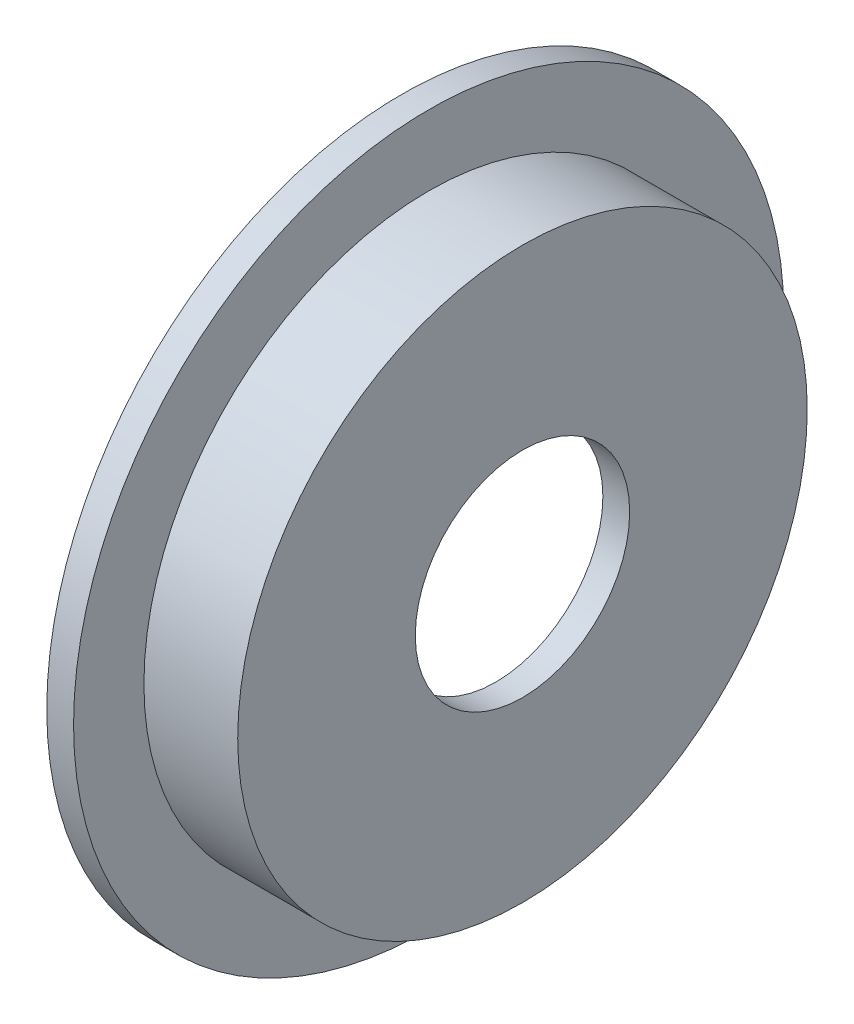
SolidWorks part; units mm, degrees
ref_plane "前视基准面" through (0, 0, 0) normal (0, 0, 1) x (1, 0, 0)
ref_plane "上视基准面" through (0, 0, 0) normal (0, 1, 0) x (1, 0, 0)
ref_plane "右视基准面" through (0, 0, 0) normal (1, 0, 0) x (0, 0, -1)
sketch "草图1" plane through (0, 0, 0) normal (0, 0, 1) x (1, 0, 0)
  line L0 (-17.5464, 0) -> (29.0653, 0) construction
  line L1 (0, -23.7077) -> (0, 22.3683) construction
  line L2 (0, 26.5) -> (2, 26.5)
  line L3 (2, 26.5) -> (2, 21.25)
  line L4 (2, 21.25) -> (9, 21.25)
  line L5 (9, 21.25) -> (9, 8)
  line L6 (0, 19.25) -> (7, 19.25)
  line L7 (7, 19.25) -> (7, 8)
  line L8 (0, 26.5) -> (0, 19.25)
  line L9 (7, 8) -> (9, 8)
  dimension "D1" = 9
  dimension "D2" = 2
  dimension "D3" = 26.5
  dimension "D5" = 7
  dimension "D7" = 8
revolve "旋转1" add sketch "草图1" angle 360 about L0
